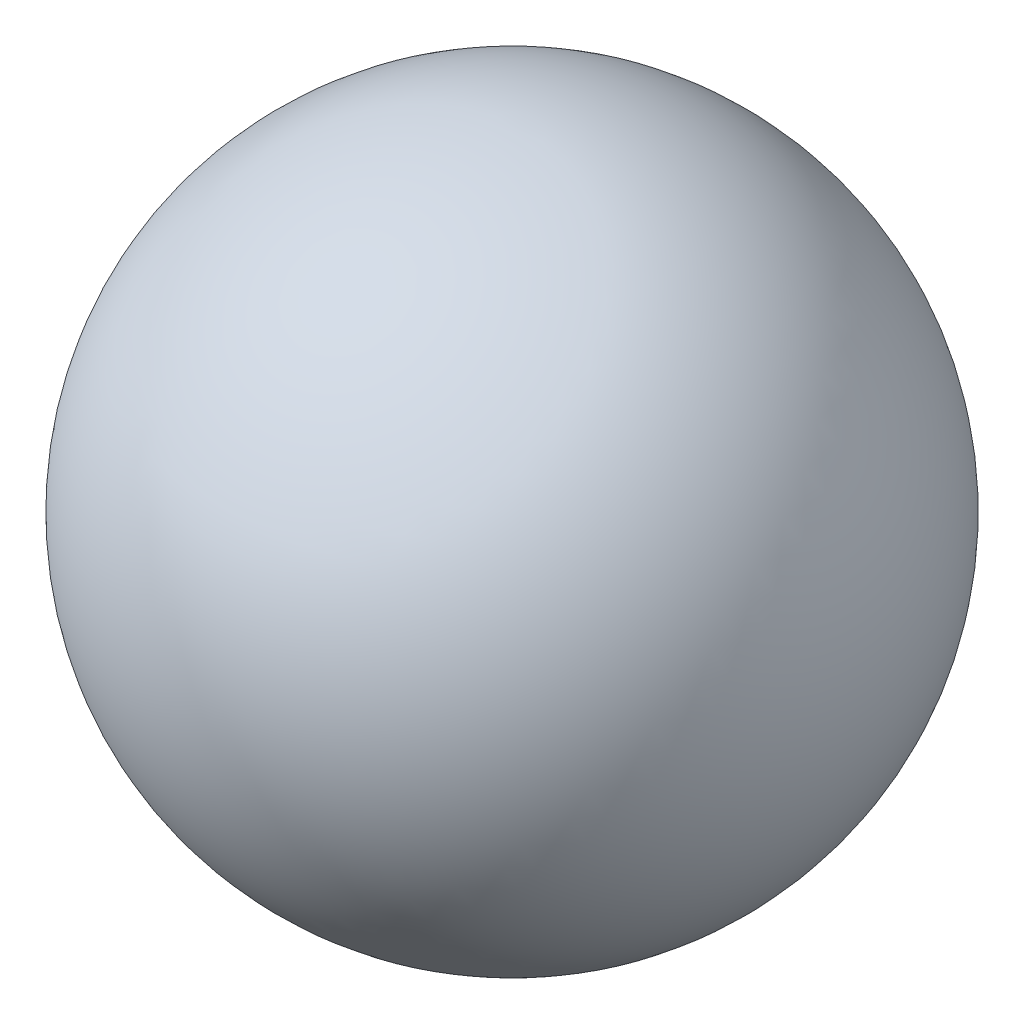
SolidWorks part; units mm, degrees
ref_plane "前基準面" through (0, 0, 0) normal (0, 0, 1) x (1, 0, 0)
ref_plane "上基準面" through (0, 0, 0) normal (0, 1, 0) x (1, 0, 0)
ref_plane "右基準面" through (0, 0, 0) normal (1, 0, 0) x (0, 0, -1)
sketch "草圖1" plane through (0, 0, 0) normal (0, 0, 1) x (1, 0, 0)
  line L0 (0, 35) -> (0, -35)
  arc A0 (0, 35) -> (0, -35) centre (0, 0) cw
  point P2 (0, 0)
  point P5 (0, 0)
  dimension "D1" = 70
revolve "旋轉1" add sketch "草圖1" angle 360 about L0
